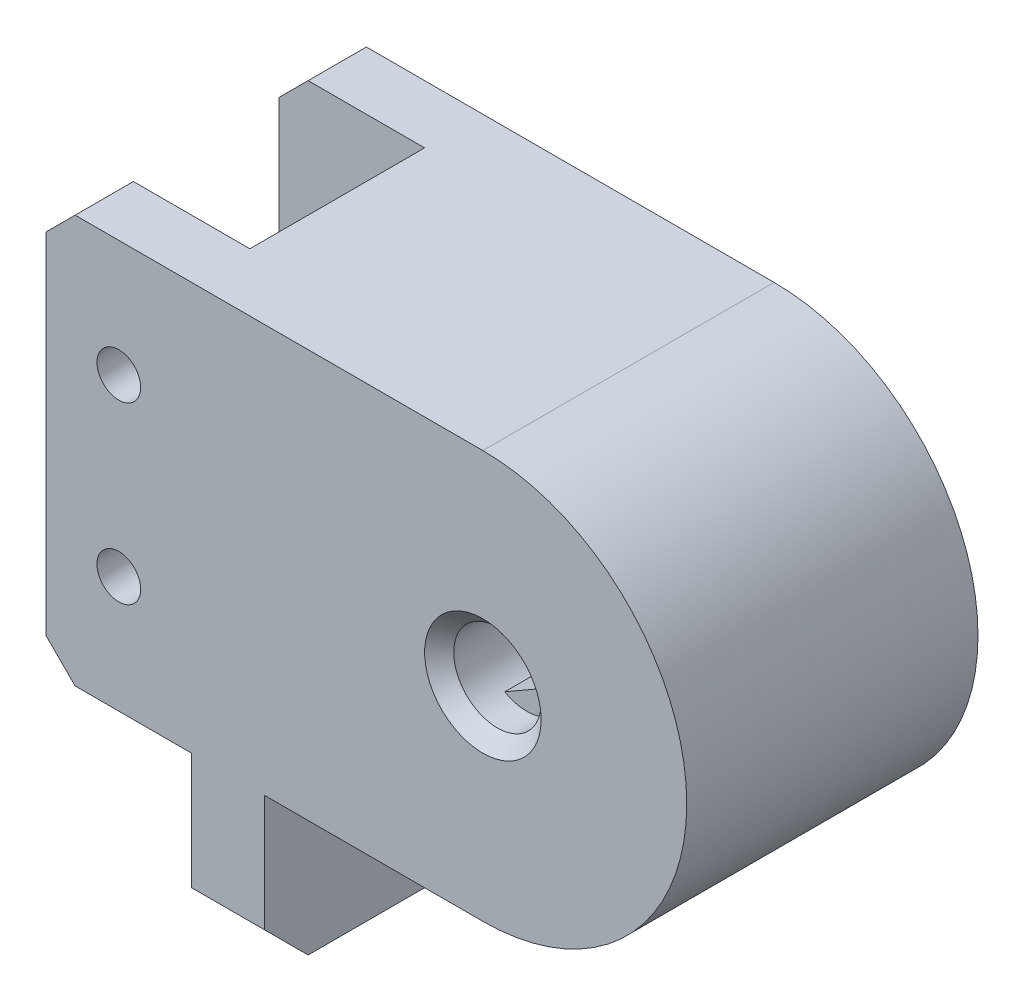
SolidWorks part; units mm, degrees
ref_plane "前视基准面" through (0, 0, 0) normal (0, 0, 1) x (1, 0, 0)
ref_plane "上视基准面" through (0, 0, 0) normal (0, 1, 0) x (1, 0, 0)
ref_plane "右视基准面" through (0, 0, 0) normal (1, 0, 0) x (0, 0, -1)
other "Configuration Table"
sketch "草图1" plane through (0, 0, 0) normal (0, 0, 1) x (1, 0, 0)
  line L1 (0, 14) -> (-30, 14)
  line L3 (0, -14) -> (-30, -14)
  line L4 (-30, 14) -> (-30, -14)
  arc A0 (0, -14) -> (0, 14) centre (0, 0) ccw
  dimension "D1" = 28
  dimension "D2" = 30
extrude "凸台-拉伸1" add sketch "草图1" along normal blind 20
sketch "草图3" plane through (0, 0, 0) normal (0, 0, -1) x (-1, 0, 0)
  line L1 (-3, 0) -> (1.5, -2.5981)
  arc A0 (1.5, -2.5981) -> (-3, 0) centre (0, 0) ccw construction
  arc A1 (1.5, -2.5981) -> (-3, 0) centre (0, 0) ccw
extrude "切除-拉伸1" cut sketch "草图3" against normal through all
sketch "草图5" plane through (0, 0, 0) normal (0, 0, -1) x (-1, 0, 0)
  circle A1 centre (0, 0) radius 3
  arc A4 (1.5, -2.5981) -> (-3, 0) centre (0, 0) ccw construction
extrude "切除-拉伸2" cut sketch "草图5" against normal blind 3
sketch "草图6" plane through (0, -14, 0) normal (0, -1, 0) x (1, 0, 0)
  line L0 (-30, 20) -> (-30, 0) construction
  line L1 (-30, 4) -> (-20, 4)
  line L2 (-30, 4) -> (-30, 16)
  line L3 (-30, 16) -> (-20, 16)
  line L4 (-20, 4) -> (-20, 16)
  line L5 (-30, 0) -> (0, 0) construction
  line L6 (-30, 20) -> (0, 20) construction
  dimension "D1" = 4
  dimension "D2" = 4
  dimension "D3" = 10
extrude "切除-拉伸3" cut sketch "草图6" against normal through all
sketch "草图7" plane through (0, 0, 0) normal (0, 0, -1) x (-1, 0, 0)
  line L0 (0, 14) -> (30, 14) construction
  line L1 (30, 14) -> (30, -14) construction
  line L3 (30, -14) -> (0, -14) construction
  point P0 (25, 6)
  point P1 (25, -6)
  dimension "D1" = 8
  dimension "D2" = 5
  dimension "D3" = 5
  dimension "D4" = 8
hole_wizard "Ø3.0mm 暗销孔1" positions "3D草图2" profile "草图8" hole size "Ø3.0" standard "GB" end condition through all
sketch3d "3D草图2"
  point P0 (-25, 6, 0)
  point P3 (-25, -6, 0)
sketch "草图8" plane through (-25, 6, 0) normal (1, 0, 0) x (0, 1, 0)
  line L0 (0, 0) -> (0, 20)
  line L1 (0, 20) -> (1.5, 20)
  line L2 (1.5, 20) -> (1.5, 0.025)
  line L3 (1.5, 0.025) -> (1.525, 0)
  line L5 (1.525, 0) -> (0, 0)
  line L6 (-1.5, 0.025) -> (-1.525, 0) construction
  line L11 (0, -6.35) -> (0, 107.95) construction
  dimension "通孔孔直径" = 3
  dimension "通孔孔深度" = 20
  dimension "近端锥形沉头孔直径" = 3.05
  dimension "近端锥形沉头孔角度" = 90
chamfer "倒角2" distance 2 angle 45 4 edges at (-30, 14, 2) (-30, 14, 18) (-30, -14, 2) (-30, -14, 18)
sketch "草图9" plane through (0, 0, 20) normal (0, 0, 1) x (1, 0, 0)
  circle A0 centre (0, 0) radius 3
  arc A1 (3, 0) -> (-1.5, -2.5981) centre (0, 0) ccw construction
extrude "切除-拉伸5" cut sketch "草图9" against normal blind 3
sketch "草图10" plane through (0, -14, 0) normal (0, -1, 0) x (1, 0, 0)
  line L0 (-28, 20) -> (0, 20) construction
  line L1 (-20, 20) -> (-15, 20)
  line L2 (-20, 20) -> (-20, 0)
  line L3 (-20, 0) -> (-15, 0)
  line L4 (-15, 20) -> (-15, 0)
  line L5 (-28, 0) -> (0, 0) construction
  line L6 (0, 20) -> (0, 0) construction
  dimension "D1" = 5
  dimension "D2" = 15
extrude "凸台-拉伸2" add sketch "草图10" along normal blind 11
chamfer "倒角3" distance 3 angle 45 2 edges at (-17.5, -25, 20) (-17.5, -25, 0)
chamfer "倒角4" distance 1 angle 45 2 edges at (-3, 0, 0) (-3, 0, 20)
